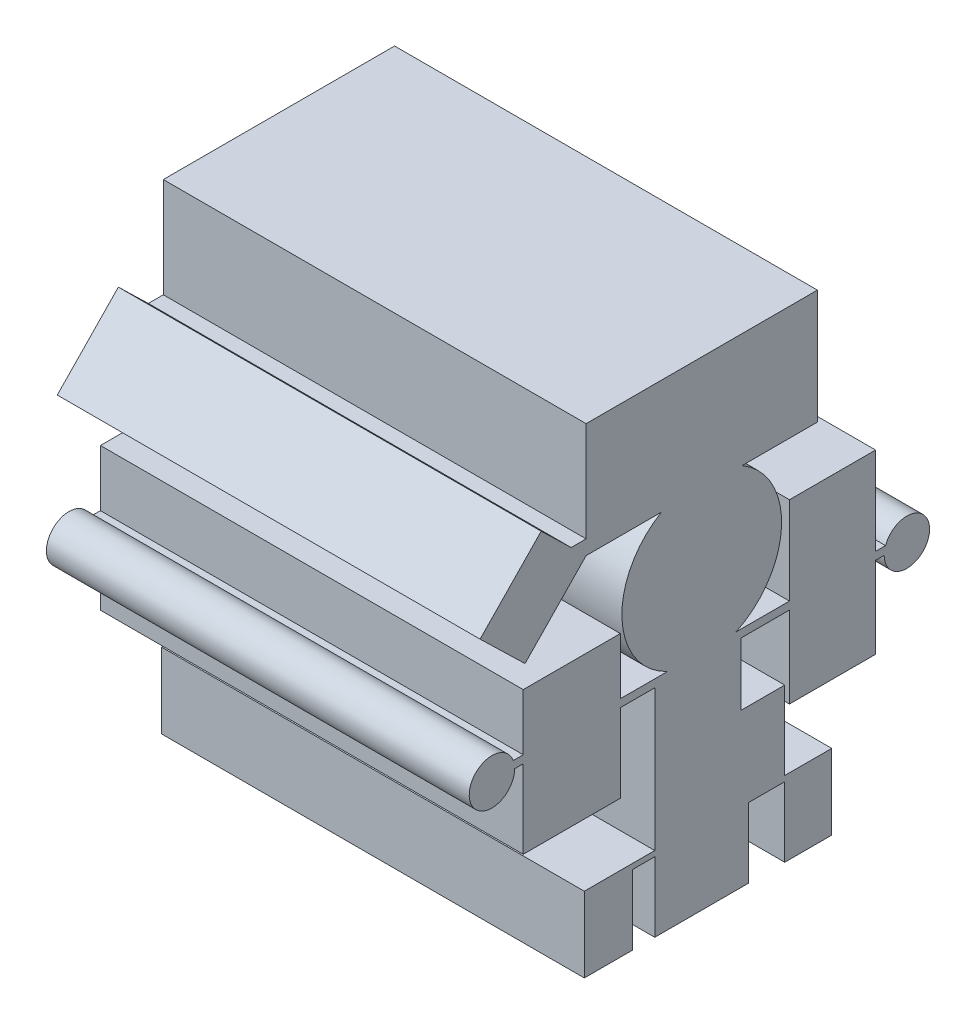
SolidWorks part; units mm, degrees
ref_plane "Front Plane"
ref_plane "Top Plane" through (0, 0, 0) normal (0, 1, 0) x (1, 0, 0)
ref_plane "Right Plane" through (0, 0, 0) normal (1, 0, 0) x (0, 0, -1)
sketch "Sketch1" plane through (0, 0, 0) normal (1, 0, 0) x (0, 0, -1)
  line L0 (410.718, 0) -> (-410.718, 0) construction
  line L1 (-112.268, 0) -> (-190.5, 0)
  line L2 (-112.268, 0) -> (-112.268, 113.2399)
  line L3 (-112.268, 121.92) -> (-190.5, 121.92)
  line L4 (-190.5, 0) -> (-190.5, 121.92)
  line L5 (0, 427.482) -> (0, -427.482) construction
  line L6 (-286.6457, 489.7513) -> (-359.5519, 560.5132)
  line L7 (-76.2, 0) -> (76.2, 0)
  line L8 (-76.2, 0) -> (-76.2, 113.2399)
  line L10 (76.2, 0) -> (76.2, 113.2399)
  line L11 (134.62, 0) -> (210.82, 0)
  line L12 (134.62, 0) -> (134.62, 113.2399)
  line L13 (134.62, 121.92) -> (210.82, 121.92)
  line L14 (210.82, 0) -> (210.82, 121.92)
  line L16 (-76.2, 121.92) -> (-76.2, 248.92)
  line L17 (63.5, 248.92) -> (134.62, 248.92)
  line L18 (134.62, 121.92) -> (134.62, 248.92)
  line L20 (-76.2, 248.92) -> (-76.2, 350.52)
  line L22 (63.5, 248.92) -> (63.5, 350.52)
  line L23 (142.24, 505.46) -> (281.94, 505.46)
  line L24 (142.24, 505.46) -> (142.24, 363.0962)
  line L25 (142.24, 218.44) -> (281.94, 218.44)
  line L26 (281.94, 505.46) -> (281.94, 363.0962)
  line L27 (-187.579, 777.24) -> (187.579, 777.24)
  line L28 (-187.579, 777.24) -> (-187.579, 615.3601)
  line L29 (-187.579, 591.82) -> (-65.5005, 591.82)
  line L30 (187.579, 777.24) -> (187.579, 591.82)
  line L33 (-132.08, 454.66) -> (-289.56, 454.66)
  line L34 (-132.08, 454.66) -> (-132.08, 363.0962)
  line L35 (-132.08, 223.266) -> (-289.56, 223.266)
  line L36 (-289.56, 454.66) -> (-289.56, 363.0962)
  line L37 (-286.6457, 489.7513) -> (-187.579, 591.82)
  line L38 (-359.5519, 560.5132) -> (-260.4852, 662.5819)
  line L39 (-211.8325, 615.3601) -> (-260.4852, 662.5819)
  line L40 (65.5005, 591.82) -> (187.579, 591.82)
  line L41 (-303.53, 350.52) -> (-289.56, 350.52)
  line L43 (-305.7437, 363.0962) -> (-289.56, 363.0962)
  line L47 (-187.579, 615.3601) -> (-211.8325, 615.3601)
  line L49 (-112.268, 121.92) -> (-76.2, 121.92)
  line L51 (-112.268, 113.2399) -> (-76.2, 113.2399)
  line L53 (55.6784, 363.0962) -> (142.24, 363.0962)
  line L54 (63.5, 350.52) -> (142.24, 350.52)
  line L55 (-132.08, 350.52) -> (-132.08, 223.266)
  line L56 (-132.08, 350.52) -> (-76.2, 350.52)
  line L57 (-132.08, 363.0962) -> (-55.6784, 363.0962)
  line L58 (-289.56, 350.52) -> (-289.56, 223.266)
  line L59 (142.24, 350.52) -> (142.24, 218.44)
  line L60 (281.94, 350.52) -> (281.94, 218.44)
  line L62 (76.2, 113.2399) -> (134.62, 113.2399)
  line L63 (281.94, 350.52) -> (295.91, 350.52)
  line L64 (281.94, 363.0962) -> (298.1237, 363.0962)
  arc A0 (-65.5005, 591.82) -> (-55.6784, 363.0962) centre (0, 480.06) ccw
  arc A1 (-305.7437, 363.0962) -> (-303.53, 350.52) centre (-340.36, 350.52) ccw
  arc A2 (295.91, 350.52) -> (298.1237, 363.0962) centre (332.74, 350.52) ccw
  arc A3 (55.6784, 363.0962) -> (65.5005, 591.82) centre (0, 480.06) ccw
  point P27 (0, 684.53)
  dimension "D14" = 259.08
  dimension "D31" = 73.66
  dimension "D33" = 73.66
  dimension "D1" = 78.232
  dimension "D2" = 190.5
  dimension "D3" = 121.92
  dimension "D4" = 152.4
  dimension "D5" = 76.2
  dimension "D6" = 121.92
  dimension "D7" = 76.2
  dimension "D8" = 121.92
  dimension "D9" = 58.42
  dimension "D10" = 0
  dimension "D11" = 127
  dimension "D12" = 101.6
  dimension "D13" = 139.7
  dimension "D15" = 287.02
  dimension "D16" = 139.7
  dimension "D17" = 78.74
  dimension "D18" = 25.4
  dimension "D19" = 185.42
  dimension "D20" = 375.158
  dimension "D21" = 0
  dimension "D22" = 63.5
  dimension "D24" = 231.394
  dimension "D25" = 157.48
  dimension "D26" = 25.4
  dimension "D27" = 132.08
  dimension "D28" = 142.24
  dimension "D29" = 101.6
  dimension "D32" = 0
  dimension "D34" = 50.8
  dimension "D35" = 50.8
  dimension "D37" = 144.6562
  dimension "D40" = 8.6801
extrude "Boss-Extrude1" add sketch "Sketch1" along normal blind 685.8
